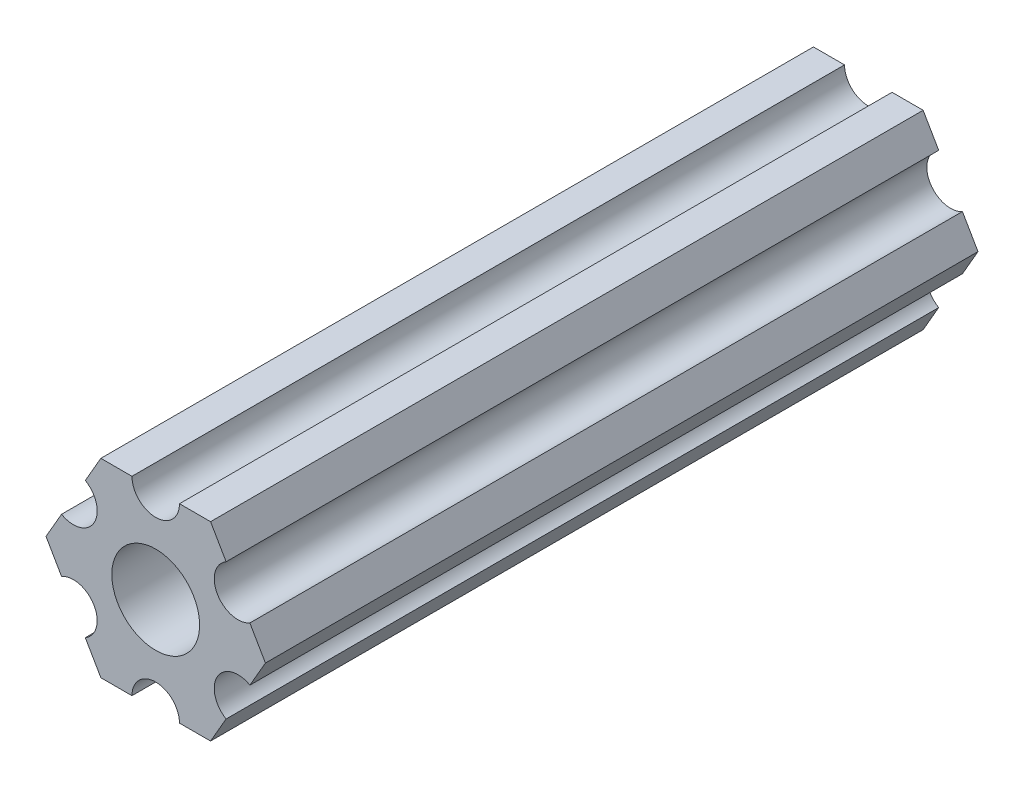
SolidWorks part; units mm, degrees
material "6061 Alloy"
ref_plane "Front Plane" through (0, 0, 0) normal (0, 0, 1) x (1, 0, 0)
ref_plane "Top Plane" through (0, 0, 0) normal (0, 1, 0) x (1, 0, 0)
ref_plane "Right Plane" through (0, 0, 0) normal (1, 0, 0) x (0, 0, -1)
ref_plane "Plane1" through (0, 0, 304.8) normal (0, 0, 1) x (1, 0, 0)
sketch "Sketch1" plane through (0, 0, 304.8) normal (0, 0, 1) x (1, 0, 0)
  line L0 (6.293, -1.8002) -> (7.3323, 0)
  line L1 (7.3323, 0) -> (6.293, 1.8002)
  line L2 (4.7055, 4.5498) -> (3.6662, 6.35)
  line L3 (3.6662, 6.35) -> (1.5875, 6.35)
  line L4 (-1.5875, 6.35) -> (-3.6662, 6.35)
  line L5 (-3.6662, 6.35) -> (-4.7055, 4.5498)
  line L6 (-6.293, 1.8002) -> (-7.3323, 0)
  line L7 (-7.3323, 0) -> (-6.293, -1.8002)
  line L8 (-4.7055, -4.5498) -> (-3.6662, -6.35)
  line L9 (-3.6662, -6.35) -> (-1.5875, -6.35)
  line L10 (1.5875, -6.35) -> (3.6662, -6.35)
  line L11 (3.6662, -6.35) -> (4.7055, -4.5498)
  arc A0 (6.293, 1.8002) -> (4.7055, 4.5498) centre (5.4993, 3.175) cw
  arc A1 (1.5875, 6.35) -> (-1.5875, 6.35) centre (0, 6.35) cw
  arc A2 (-4.7055, 4.5498) -> (-6.293, 1.8002) centre (-5.4993, 3.175) cw
  arc A3 (-6.293, -1.8002) -> (-4.7055, -4.5498) centre (-5.4993, -3.175) cw
  arc A4 (-1.5875, -6.35) -> (1.5875, -6.35) centre (0, -6.35) cw
  arc A5 (4.7055, -4.5498) -> (6.293, -1.8002) centre (5.4993, -3.175) cw
  circle A6 centre (0, 0) radius 2.9337
extrude "Boss-Extrude1" add sketch "Sketch1" against normal blind 47.625
